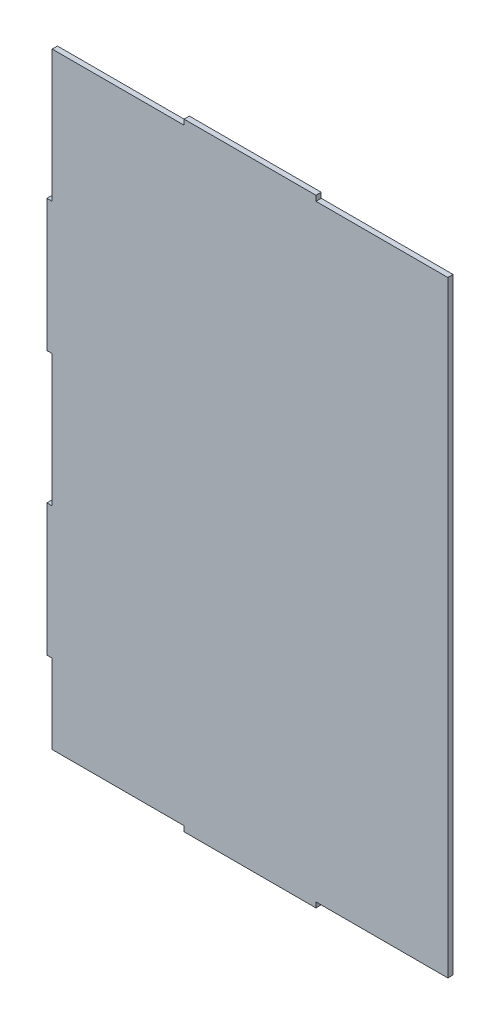
SolidWorks part; units mm, degrees
ref_plane "前视基准面" through (0, 0, 0) normal (0, 0, 1) x (1, 0, 0)
ref_plane "上视基准面" through (0, 0, 0) normal (0, 1, 0) x (1, 0, 0)
ref_plane "右视基准面" through (0, 0, 0) normal (1, 0, 0) x (0, 0, -1)
other "Configuration Table"
sketch "草图2" plane through (0, 0, 0) normal (0, 0, 1) x (1, 0, 0)
  line L0 (-152, -170) -> (-148, -170)
  line L1 (-152, -70) -> (-152, -170)
  line L2 (-148, -70) -> (-152, -70)
  line L3 (-148, 30) -> (-148, -70)
  line L4 (-152, 30) -> (-148, 30)
  line L5 (-152, 130) -> (-152, 30)
  line L6 (-148, 130) -> (-152, 130)
  line L7 (-148, 230) -> (-148, 130)
  line L8 (152, 230) -> (52, 230)
  line L9 (-48, 230) -> (-148, 230)
  line L10 (152, 130) -> (152, 230)
  line L12 (152, -230) -> (152, -170)
  line L13 (52, -230) -> (152, -230)
  line L14 (52, -234) -> (52, -230)
  line L15 (-48, -234) -> (52, -234)
  line L16 (-48, -230) -> (-48, -234)
  line L17 (-148, -230) -> (-48, -230)
  line L18 (-148, -170) -> (-148, -230)
  line L24 (52, 234) -> (52, 230)
  line L25 (-48, 234) -> (52, 234)
  line L26 (-48, 230) -> (-48, 234)
  line L28 (152, 130) -> (152, -170)
extrude "凸台-拉伸1" add sketch "草图2" along normal blind 4
